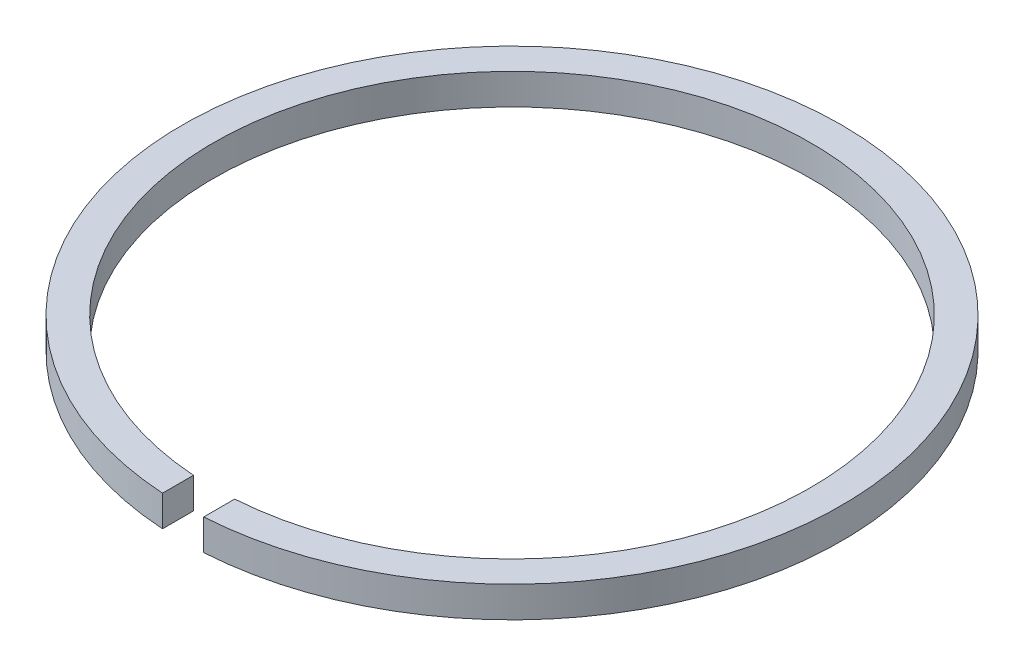
SolidWorks part; units mm, degrees
ref_plane "Front Plane" through (0, 0, 0) normal (0, 0, 1) x (1, 0, 0)
ref_plane "Top Plane" through (0, 0, 0) normal (0, 1, 0) x (1, 0, 0)
ref_plane "Right Plane" through (0, 0, 0) normal (1, 0, 0) x (0, 0, -1)
sketch "Sketch1" plane through (0, 0, 0) normal (0, 1, 0) x (1, 0, 0)
  circle A0 centre (0, 0) radius 14.5
  circle A1 centre (0, 0) radius 16
  dimension "D1" = 32
  dimension "D2" = 29
extrude "Boss-Extrude1" add sketch "Sketch1" along normal mid plane 1.5
sketch "Sketch3" plane through (0, 0.75, 0) normal (0, 1, 0) x (1, 0, 0)
  line L1 (-1, -13.5024) -> (1, -13.5024)
  line L2 (-1, -13.5024) -> (-1, -17.5024)
  line L3 (-1, -17.5024) -> (1, -17.5024)
  line L4 (1, -13.5024) -> (1, -17.5024)
  point P4 (0, -13.5024)
  dimension "D1" = 2
  dimension "D2" = 4
extrude "Cut-Extrude2" cut sketch "Sketch3" against normal through all
